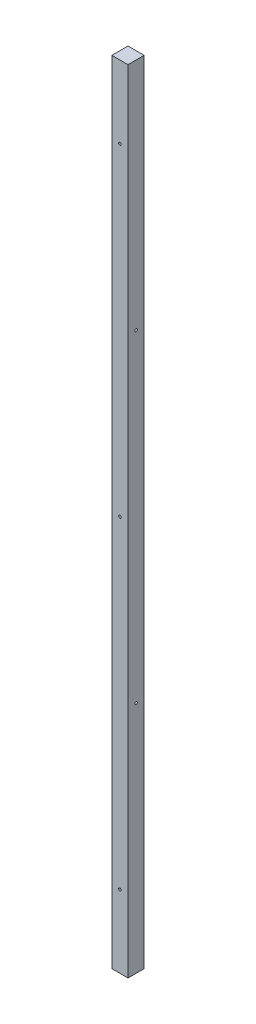
SolidWorks part; units mm, degrees
ref_plane "Спереди" through (0, 0, 0) normal (0, 0, 1) x (1, 0, 0)
ref_plane "Сверху" through (0, 0, 0) normal (0, 1, 0) x (1, 0, 0)
ref_plane "Справа" through (0, 0, 0) normal (1, 0, 0) x (0, 0, -1)
other "Configuration Table"
sketch "Эскиз1" plane through (0, 0, 0) normal (0, 1, 0) x (1, 0, 0)
  line L1 (25, 25) -> (-25, 25)
  line L2 (25, 25) -> (25, -25)
  line L3 (25, -25) -> (-25, -25)
  line L4 (-25, 25) -> (-25, -25)
  line L5 (25, 25) -> (-25, -25) construction
  line L6 (25, -25) -> (-25, 25) construction
  point P0 (0, 0)
extrude "Бобышка-Вытянуть1" add sketch "Эскиз1" along normal blind 2450
sketch "Эскиз10" plane through (0, 0, -25) normal (0, 0, -1) x (-1, 0, 0)
  line L0 (0, 2450) -> (0, 2225) construction
  line L1 (-25, 2450) -> (25, 2450) construction
  line L2 (0, 0) -> (0, 225) construction
  line L3 (0, 2450) -> (0, 1225) construction
  circle A0 centre (0, 1225) radius 4
  circle A1 centre (0, 2225) radius 4
  circle A2 centre (0, 225) radius 4
extrude "Вырез-Вытянуть8" cut sketch "Эскиз10" against normal blind 50
sketch "Эскиз11" plane through (25, 0, 0) normal (1, 0, 0) x (0, 0, -1)
  line L0 (0, 2450) -> (0, 1725) construction
  line L1 (-25, 2450) -> (25, 2450) construction
  line L2 (0, 0) -> (0, 725) construction
  circle A0 centre (0, 1725) radius 4
  circle A1 centre (0, 725) radius 4
extrude "Вырез-Вытянуть9" cut sketch "Эскиз11" against normal blind 50
